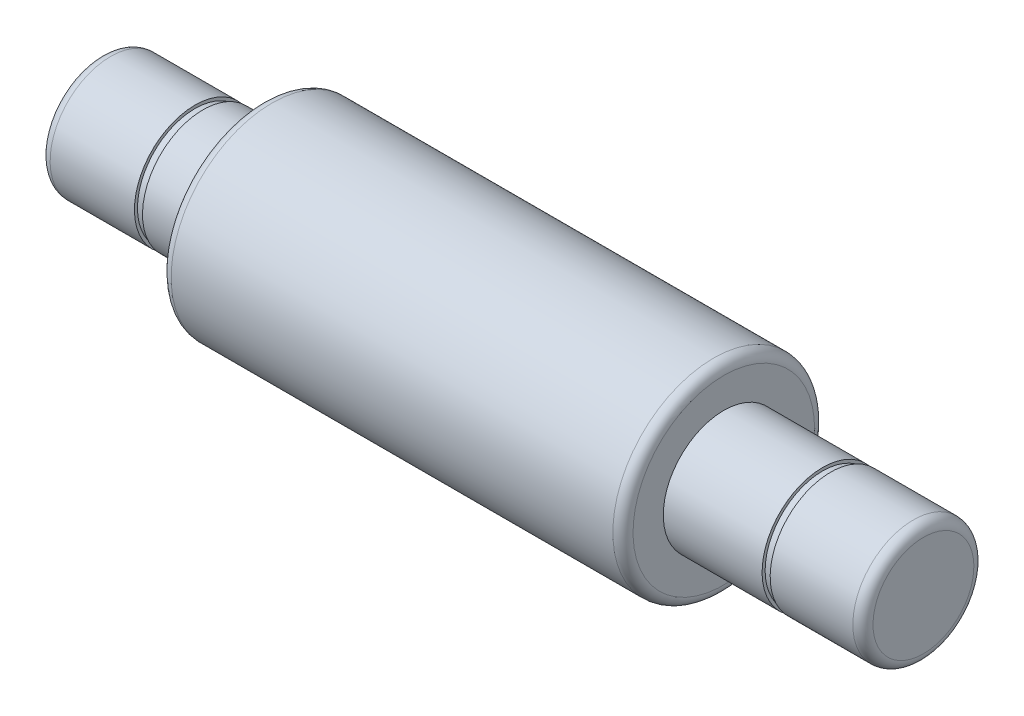
SolidWorks part; units mm, degrees
material "AISI 4340 Steel, normalized"
ref_plane "Front Plane" through (0, 0, 0) normal (0, 0, 1) x (1, 0, 0)
ref_plane "Top Plane" through (0, 0, 0) normal (0, 1, 0) x (1, 0, 0)
ref_plane "Right Plane" through (0, 0, 0) normal (1, 0, 0) x (0, 0, -1)
sketch "Sketch1" plane through (0, 0, 0) normal (0, 0, 1) x (1, 0, 0)
  line L0 (0, 0) -> (0, 5) construction
  line L1 (-12.4, 5) -> (12.4, 5)
  line L2 (12.4, 3) -> (15.32, 3)
  line L3 (20.4, 3) -> (20.4, 0)
  line L4 (12.4, 5) -> (12.4, 3)
  line L5 (-20.4, 0) -> (20.4, 0)
  line L6 (-12.4, 5) -> (-12.4, 3)
  line L7 (-20.4, 3) -> (-20.4, 0)
  line L8 (-12.4, 3) -> (-15.32, 3)
  line L9 (15.32, 3) -> (15.32, 2.85)
  line L10 (15.32, 2.85) -> (15.82, 2.85)
  line L11 (15.82, 2.85) -> (15.82, 3)
  line L12 (15.82, 3) -> (20.4, 3)
  line L13 (-15.82, 2.85) -> (-15.82, 3)
  line L14 (-15.32, 2.85) -> (-15.82, 2.85)
  line L15 (-15.32, 3) -> (-15.32, 2.85)
  line L16 (-15.82, 3) -> (-20.4, 3)
  point P6 (0, 5)
  dimension "D1" = 12.4
  dimension "D2" = 5
  dimension "D3" = 3
  dimension "D4" = 8
  dimension "D5" = 2.85
  dimension "D6" = 0.5
  dimension "D7" = 2.92
revolve "Revolve1" add sketch "Sketch1" angle 360 about L5
sketch "Sketch2" plane through (12.4, 0, 0) normal (1, 0, 0) x (0, 0, -1)
  circle A0 centre (0, 0) radius 5
  circle A1 centre (0, 0) radius 3
extrude "Cut-Extrude2" cut sketch "Sketch2" against normal blind 1.9
sketch "Sketch3" plane through (10.5, 0, 0) normal (1, 0, 0) x (0, 0, -1)
  circle A0 centre (0, 0) radius 5
  circle A1 centre (0, 0) radius 3
fillet "Fillet1" radius 0.5 4 edges at (-20.4, -3, 0) (-12.4, -5, 0) (20.4, -3, 0) (10.5, 5, 0)
sketch "Sketch4" plane through (-15.82, 0, 0) normal (1, 0, 0) x (0, 0, -1)
  circle A0 centre (0, 0) radius 3
  circle A1 centre (0, 0) radius 2.85
extrude "Boss-Extrude2" add sketch "Sketch4" along normal blind 0.1
sketch "Sketch6" plane through (15.82, 0, 0) normal (-1, 0, 0) x (0, 0, 1)
  circle A0 centre (0, 0) radius 3
  circle A1 centre (0, 0) radius 2.85
extrude "Boss-Extrude3" add sketch "Sketch6" along normal blind 0.02
sketch "Sketch7" plane through (15.32, 0, 0) normal (1, 0, 0) x (0, 0, -1)
  circle A0 centre (0, 0) radius 3
  circle A1 centre (0, 0) radius 2.85
extrude "Boss-Extrude4" add sketch "Sketch7" along normal blind 0.08
